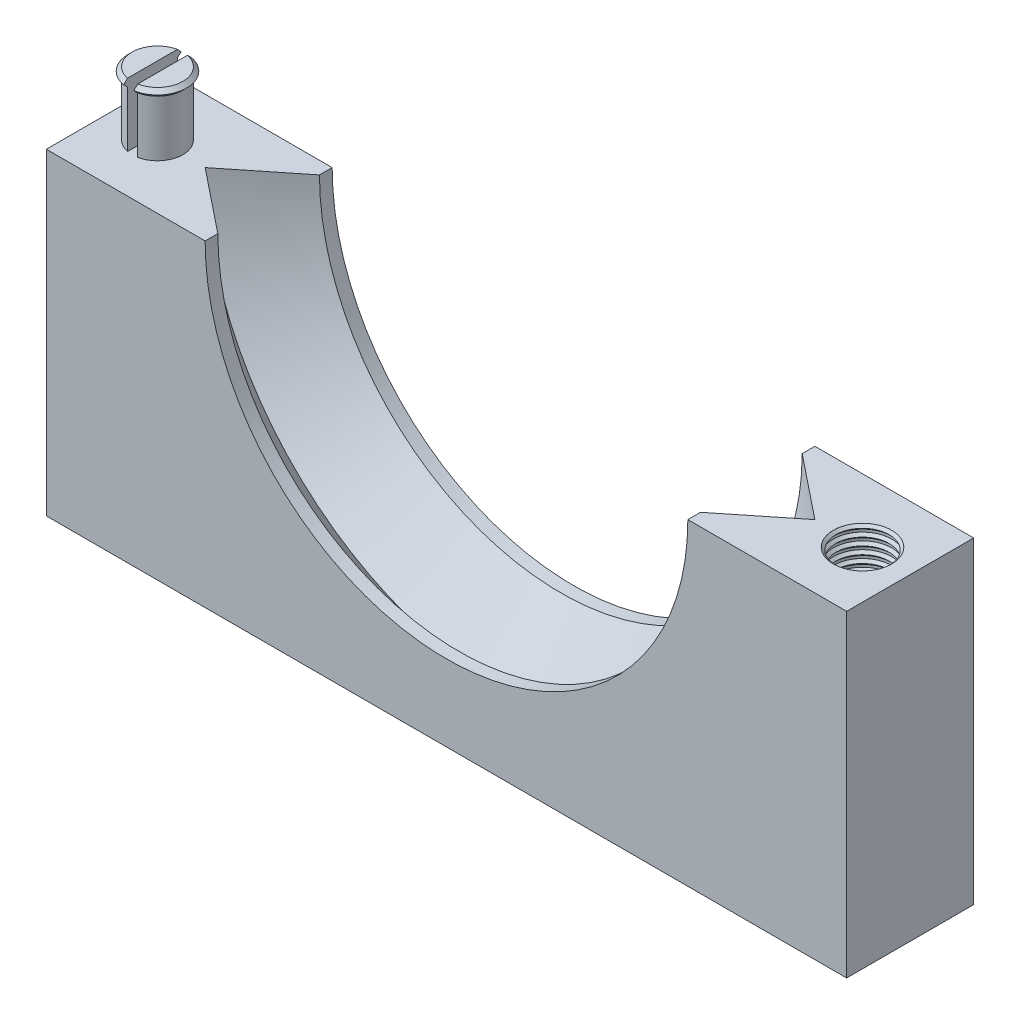
SolidWorks part; units mm, degrees
ref_plane "Front Plane" through (0, 0, 0) normal (0, 0, 1) x (1, 0, 0)
ref_plane "Top Plane" through (0, 0, 0) normal (0, 1, 0) x (1, 0, 0)
ref_plane "Right Plane" through (0, 0, 0) normal (1, 0, 0) x (0, 0, -1)
sketch "Sketch1" plane through (0, 0, 0) normal (0, 0, 1) x (1, 0, 0)
  line L0 (-40.005, 0) -> (40.005, 0)
  line L1 (40.005, 0) -> (40.005, 31.75)
  line L2 (40.005, 31.75) -> (24.13, 31.75)
  line L3 (-24.13, 31.75) -> (-40.005, 31.75)
  line L4 (-40.005, 31.75) -> (-40.005, 0)
  arc A0 (24.13, 31.75) -> (-24.13, 31.75) centre (0, 31.75) cw
  point P7 (0, 0)
  dimension "D2" = 24.13
  dimension "D1" = 31.75
  dimension "D3" = 15.875
extrude "Boss-Extrude1" add sketch "Sketch1" along normal blind 12.7
sketch "Sketch2" plane through (0, 31.75, 0) normal (0, 1, 0) x (1, 0, 0)
  line L0 (24.13, -11.43) -> (30.48, -6.35)
  line L2 (24.13, -12.7) -> (24.13, 0) construction
  line L3 (30.48, -6.35) -> (24.13, -1.27)
  line L4 (22.8654, -6.35) -> (40.005, -6.35) construction
  line L5 (24.13, -1.27) -> (24.13, -11.43)
  line L6 (40.005, -12.7) -> (40.005, 0) construction
  line L7 (0, 0) -> (0, -23.6383) construction
  dimension "D1" = 10.16
  dimension "D2" = 6.35
revolve "Cut-Revolve1" cut sketch "Sketch2" angle 360 about L7
sketch "Sketch6" plane through (0, 31.75, 0) normal (0, 1, 0) x (1, 0, 0)
  line L0 (30.48, -6.35) -> (40.005, -6.35) construction
  line L1 (40.005, -12.7) -> (40.005, 0) construction
  circle A0 centre (35.2425, -6.35) radius 2.921
  dimension "D1" = 5.842
extrude "Cut-Extrude2" cut sketch "Sketch6" against normal blind 9.525
sketch "Sketch11" plane through (0, 31.75, 0) normal (0, 1, 0) x (1, 0, 0)
  line L0 (30.48, -6.35) -> (40.005, -6.35) construction
  line L1 (40.005, -12.7) -> (40.005, 0) construction
ref_plane "Plane1" through (0, 0, 6.35) normal (0, 0, 1) x (1, 0, 0)
sketch "Sketch15" plane through (0, 0, 6.35) normal (0, 0, 1) x (1, 0, 0)
  line L0 (-37.7825, 31.75) -> (-37.7825, 37.338)
  line L1 (-24.13, 31.75) -> (-40.005, 31.75) construction
  line L2 (-37.7825, 37.338) -> (-38.1635, 37.719)
  line L3 (-38.1635, 37.719) -> (-37.7825, 38.1)
  line L4 (-37.7825, 38.1) -> (-35.2425, 38.1)
  line L5 (-35.2425, 38.1) -> (-35.2425, 31.75)
  line L6 (-35.2425, 31.75) -> (-37.7825, 31.75)
  line L7 (-40.005, 31.75) -> (-40.005, 0) construction
  line L8 (-37.7825, 38.1) -> (-37.7825, 37.338) construction
  line L9 (-30.48, 31.75) -> (-40.005, 31.75) construction
  dimension "D1" = 2.54
  dimension "D3" = 6.35
  dimension "D4" = 90
  dimension "D5" = 2.921
revolve "Revolve2" add sketch "Sketch15" angle 360 about L5
sketch "Sketch12" plane through (0, 0, 6.35) normal (0, 0, 1) x (1, 0, 0)
  line L0 (35.2425, 31.75) -> (35.2425, 26.6144) construction
  line L1 (30.48, 31.75) -> (40.005, 31.75) construction
  line L2 (32.3215, 30.48) -> (32.5755, 30.734)
  line L3 (32.3215, 31.242) -> (32.5755, 31.496)
  line L4 (32.5755, 31.496) -> (32.3215, 31.75)
  line L5 (32.3215, 31.75) -> (32.3215, 31.242)
  line L6 (35.2425, 31.75) -> (32.3215, 31.75) construction
  line L7 (32.5755, 30.734) -> (32.3215, 30.988)
  line L8 (32.3215, 30.988) -> (32.3215, 30.48)
  line L9 (32.3215, 29.718) -> (32.5755, 29.972)
  line L10 (32.5755, 29.972) -> (32.3215, 30.226)
  line L11 (32.3215, 30.226) -> (32.3215, 29.718)
  line L12 (32.3215, 28.956) -> (32.5755, 29.21)
  line L13 (32.5755, 29.21) -> (32.3215, 29.464)
  line L14 (32.3215, 29.464) -> (32.3215, 28.956)
  line L15 (32.3215, 28.194) -> (32.5755, 28.448)
  line L16 (32.5755, 28.448) -> (32.3215, 28.702)
  line L17 (32.3215, 28.702) -> (32.3215, 28.194)
  line L18 (32.3215, 27.432) -> (32.5755, 27.686)
  line L19 (32.5755, 27.686) -> (32.3215, 27.94)
  line L20 (32.3215, 27.94) -> (32.3215, 27.432)
  line L21 (32.3215, 26.67) -> (32.5755, 26.924)
  line L22 (32.5755, 26.924) -> (32.3215, 27.178)
  line L23 (32.3215, 27.178) -> (32.3215, 26.67)
  line L24 (32.3215, 25.908) -> (32.5755, 26.162)
  line L25 (32.5755, 26.162) -> (32.3215, 26.416)
  line L26 (32.3215, 26.416) -> (32.3215, 25.908)
  line L27 (32.3215, 25.146) -> (32.5755, 25.4)
  line L28 (32.5755, 25.4) -> (32.3215, 25.654)
  line L29 (32.3215, 25.654) -> (32.3215, 25.146)
  line L30 (32.3215, 24.384) -> (32.5755, 24.638)
  line L31 (32.5755, 24.638) -> (32.3215, 24.892)
  line L32 (32.3215, 24.892) -> (32.3215, 24.384)
  line L33 (32.3215, 23.622) -> (32.5755, 23.876)
  line L34 (32.5755, 23.876) -> (32.3215, 24.13)
  line L35 (32.3215, 24.13) -> (32.3215, 23.622)
  line L36 (32.3215, 22.86) -> (32.5755, 23.114)
  line L37 (32.5755, 23.114) -> (32.3215, 23.368)
  line L38 (32.3215, 23.368) -> (32.3215, 22.86)
  line L39 (32.3215, 22.098) -> (32.5755, 22.352)
  line L40 (32.5755, 22.352) -> (32.3215, 22.606)
  line L41 (32.3215, 22.606) -> (32.3215, 22.098)
  line L42 (32.3215, 21.336) -> (32.5755, 21.59)
  line L43 (32.5755, 21.59) -> (32.3215, 21.844)
  line L44 (32.3215, 21.844) -> (32.3215, 21.336)
  line L45 (32.3215, 20.574) -> (32.5755, 20.828)
  line L46 (32.5755, 20.828) -> (32.3215, 21.082)
  line L47 (32.3215, 21.082) -> (32.3215, 20.574)
  line L48 (32.3215, 19.812) -> (32.5755, 20.066)
  line L49 (32.5755, 20.066) -> (32.3215, 20.32)
  line L50 (32.3215, 20.32) -> (32.3215, 19.812)
  line L51 (32.3215, 19.05) -> (32.5755, 19.304)
  line L52 (32.5755, 19.304) -> (32.3215, 19.558)
  line L53 (32.3215, 19.558) -> (32.3215, 19.05)
  line L54 (32.3215, 18.288) -> (32.5755, 18.542)
  line L55 (32.5755, 18.542) -> (32.3215, 18.796)
  line L56 (32.3215, 18.796) -> (32.3215, 18.288)
  line L57 (32.3215, 17.526) -> (32.5755, 17.78)
  line L58 (32.5755, 17.78) -> (32.3215, 18.034)
  line L59 (32.3215, 18.034) -> (32.3215, 17.526)
  line L60 (32.3215, 16.764) -> (32.5755, 17.018)
  line L61 (32.5755, 17.018) -> (32.3215, 17.272)
  line L62 (32.3215, 17.272) -> (32.3215, 16.764)
  dimension "D1" = 2.921
  dimension "D2" = 0.508
  dimension "D3" = 90
  dimension "D4" = 20
revolve "Revolve1" add sketch "Sketch12" angle 360 about L0
sketch "Sketch16" plane through (0, 38.1, 0) normal (0, 1, 0) x (1, 0, 0)
  line L1 (-35.7505, -11.9418) -> (-34.7345, -11.9418)
  line L2 (-35.7505, -11.9418) -> (-35.7505, -0.7582)
  line L3 (-35.7505, -0.7582) -> (-34.7345, -0.7582)
  line L4 (-34.7345, -11.9418) -> (-34.7345, -0.7582)
  line L5 (-35.7505, -11.9418) -> (-34.7345, -0.7582) construction
  line L6 (-35.7505, -0.7582) -> (-34.7345, -11.9418) construction
  point P0 (-35.2425, -6.35)
  dimension "D1" = 1.016
extrude "Cut-Extrude3" cut sketch "Sketch16" against normal up to surface (6.35 mm away) up to face at (-35.2425, 31.75, 8.89)
